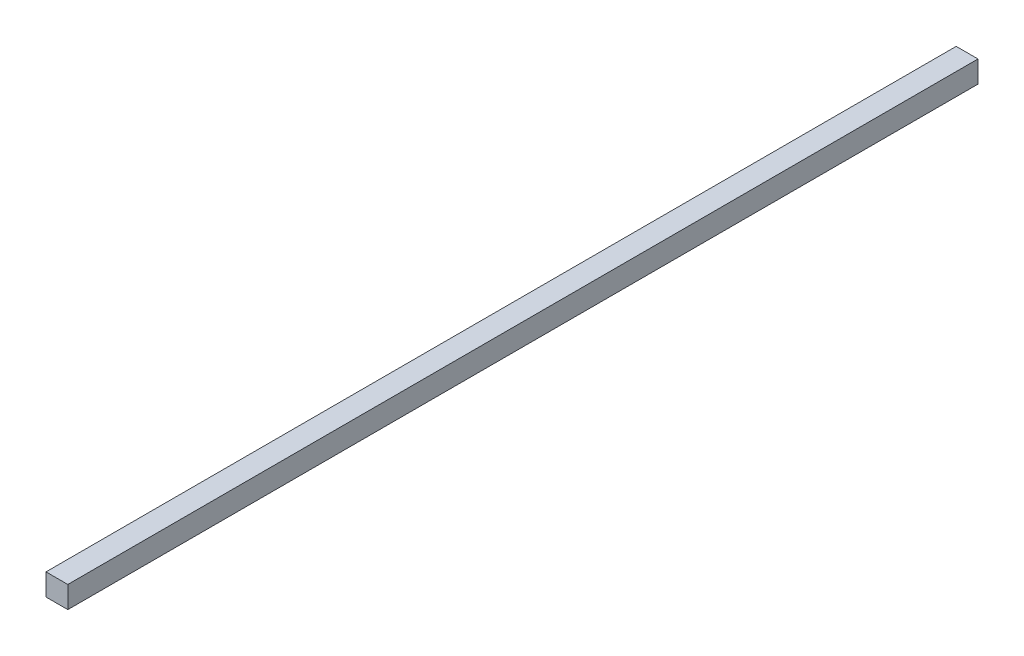
SolidWorks part; units mm, degrees
material "AISI Type A2 Tool Steel"
ref_plane "Front Plane" through (0, 0, 0) normal (0, 0, 1) x (1, 0, 0)
ref_plane "Top Plane" through (0, 0, 0) normal (0, 1, 0) x (1, 0, 0)
ref_plane "Right Plane" through (0, 0, 0) normal (1, 0, 0) x (0, 0, -1)
sketch "Sketch1" plane through (0, 0, 0) normal (0, 0, 1) x (1, 0, 0)
  line L0 (-3.175, 0) -> (3.175, 0) construction
  line L1 (0, -3.175) -> (0, 3.175) construction
  line L5 (-3.175, 3.175) -> (3.175, 3.175) construction
  line L7 (-3.175, 3.175) -> (-3.175, -3.175) construction
  line L8 (3.175, -3.175) -> (3.175, 3.175) construction
  line L13 (-3.175, -3.175) -> (3.175, -3.175) construction
  point P0 (0, 0)
  point P4 (0, 0)
  point P9 (0, 0)
  point P22 (0, 3.175)
  dimension "Thickness" = 6.35
  dimension "D1" = 6.35
sketch "Sketch2" plane through (0, 0, 0) normal (0, 1, 0) x (0, 0, -1)
  line L0 (132.5, 0) -> (-132.5, 0) construction
  line L2 (-132.5, 3.175) -> (132.5, 3.175) construction
  line L3 (-132.5, 3.175) -> (-132.5, -3.175) construction
  line L4 (-132.5, -3.175) -> (132.5, -3.175) construction
  line L5 (132.5, 3.175) -> (132.5, -3.175) construction
  line L6 (-132.5, 3.175) -> (132.5, -3.175) construction
  line L7 (-132.5, -3.175) -> (132.5, 3.175) construction
  point P4 (0, 0)
  point P7 (0, 0)
  point P12 (-122.975, 3.175)
  point P13 (122.975, 3.175)
  dimension "Length" = 265
  dimension "Width" = 6.35
  dimension "D1" = 9.525
  dimension "D2" = 9.525
sketch "Sketch3" plane through (0, 0, 0) normal (0, 0, 1) x (1, 0, 0)
  line L3 (-3.175, 3.175) -> (3.175, 3.175)
  line L17 (3.175, 3.175) -> (3.175, -3.175)
  line L18 (3.175, -3.175) -> (-3.175, -3.175)
  line L19 (-3.175, -3.175) -> (-3.175, 3.175)
extrude "Boss-Extrude1" add sketch "Sketch3" along normal mid plane 265
equation "\"D1@Boss-Extrude1\" = \"Length@Sketch2\""
equation "\"D1@Sketch1\"=\"Width@Sketch2\""
equation "\"D1@Sketch2\"=\"Width@Sketch2\"*1.5"
equation "\"D2@Sketch2\"=\"D1@Sketch2\""
